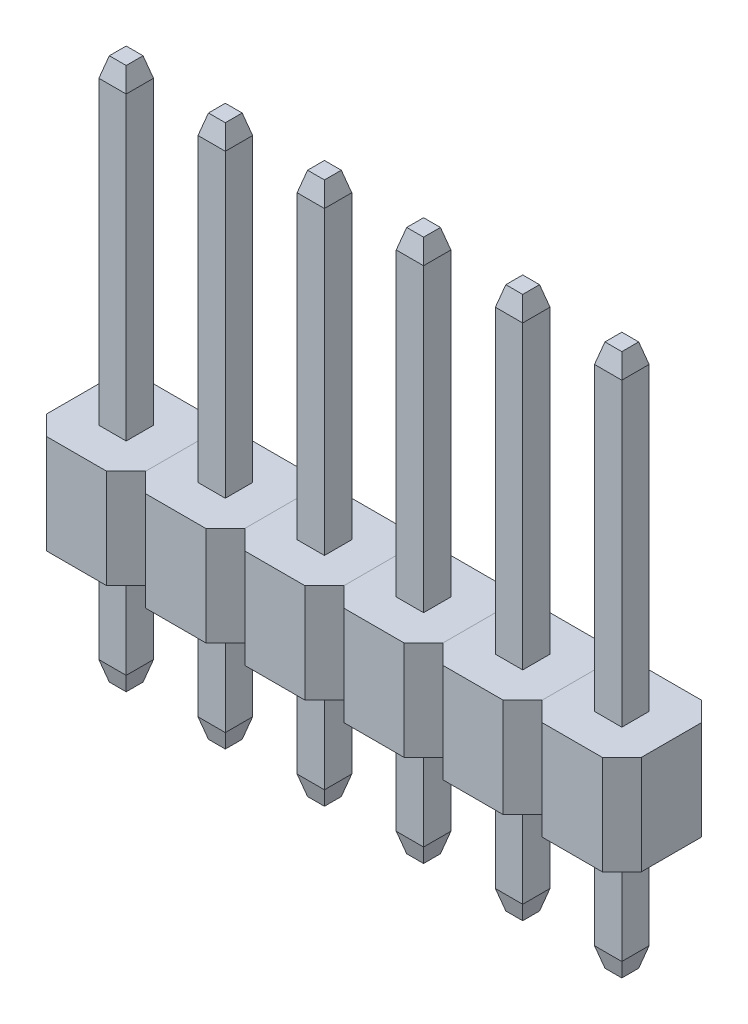
SolidWorks part; units mm, degrees
ref_plane "Front Plane" through (0, 0, 0) normal (0, 0, 1) x (1, 0, 0)
ref_plane "Top Plane" through (0, 0, 0) normal (0, 1, 0) x (1, 0, 0)
ref_plane "Right Plane" through (0, 0, 0) normal (1, 0, 0) x (0, 0, -1)
sketch "Sketch3" plane through (0, 0, 0) normal (0, 1, 0) x (1, 0, 0)
  line L1 (-1.27, 1.27) -> (1.27, 1.27)
  line L2 (-1.27, 1.27) -> (-1.27, -1.27)
  line L3 (-1.27, -1.27) -> (1.27, -1.27)
  line L4 (1.27, 1.27) -> (1.27, -1.27)
  line L5 (-1.27, 1.27) -> (1.27, -1.27) construction
  line L6 (-1.27, -1.27) -> (1.27, 1.27) construction
  line L7 (0.3175, -0.3175) -> (-0.3175, -0.3175)
  line L8 (0.3175, -0.3175) -> (0.3175, 0.3175)
  line L9 (0.3175, 0.3175) -> (-0.3175, 0.3175)
  line L10 (-0.3175, -0.3175) -> (-0.3175, 0.3175)
  line L11 (0.3175, -0.3175) -> (-0.3175, 0.3175) construction
  line L12 (0.3175, 0.3175) -> (-0.3175, -0.3175) construction
  point P0 (0, 0)
  point P7 (0, 0)
  dimension "D1" = 2.54
  dimension "D2" = 0.635
extrude "Boss-Extrude1" add sketch "Sketch3" along normal mid plane 2.54
chamfer "Chamfer1" distance 0.5 angle 45 4 edges at (-1.27, 0, 1.27) (-1.27, 0, -1.27) (1.27, 0, -1.27) (1.27, 0, 1.27)
sketch "Sketch5" plane through (0, 1.27, 0) normal (0, 1, 0) x (1, 0, 0)
  line L1 (0.35, -0.35) -> (-0.35, -0.35)
  line L2 (0.35, -0.35) -> (0.35, 0.35)
  line L3 (0.35, 0.35) -> (-0.35, 0.35)
  line L4 (-0.35, -0.35) -> (-0.35, 0.35)
  line L5 (0.35, -0.35) -> (-0.35, 0.35) construction
  line L6 (0.35, 0.35) -> (-0.35, -0.35) construction
  point P0 (0, 0)
  dimension "D1" = 0.7
extrude "Boss-Extrude2" add sketch "Sketch5" along normal blind 7.7 and the other way blind 5.2 separate body
sketch "Sketch6" plane through (0, 8.97, 0) normal (0, 1, 0) x (1, 0, 0)
  line L4 (-0.35, 0.35) -> (-0.35, -0.35)
  line L5 (-0.35, -0.35) -> (0.35, -0.35)
  line L6 (0.35, -0.35) -> (0.35, 0.35)
  line L7 (0.35, 0.35) -> (-0.35, 0.35)
  line L8 (-0.35, 0.35) -> (-0.35, -0.35)
  line L9 (-0.35, -0.35) -> (0.35, -0.35)
  line L10 (0.35, -0.35) -> (0.35, 0.35)
  line L11 (0.35, 0.35) -> (-0.35, 0.35)
  dimension "D1" = 0
extrude "Boss-Extrude3" add sketch "Sketch6" along normal blind 0.5 draft 15
sketch "Sketch7" plane through (0, -3.93, 0) normal (0, -1, 0) x (1, 0, 0)
  line L4 (-0.35, 0.35) -> (-0.35, -0.35)
  line L5 (-0.35, -0.35) -> (0.35, -0.35)
  line L6 (0.35, -0.35) -> (0.35, 0.35)
  line L7 (0.35, 0.35) -> (-0.35, 0.35)
  line L8 (-0.35, 0.35) -> (-0.35, -0.35)
  line L9 (-0.35, -0.35) -> (0.35, -0.35)
  line L10 (0.35, -0.35) -> (0.35, 0.35)
  line L11 (0.35, 0.35) -> (-0.35, 0.35)
  dimension "D1" = 0
extrude "Boss-Extrude4" add sketch "Sketch7" along normal blind 0.5 draft 15
pattern_linear "LPattern1" count 6 spacing 2.54 along (1, 0, 0) of "Boss-Extrude1", "Boss-Extrude2"
